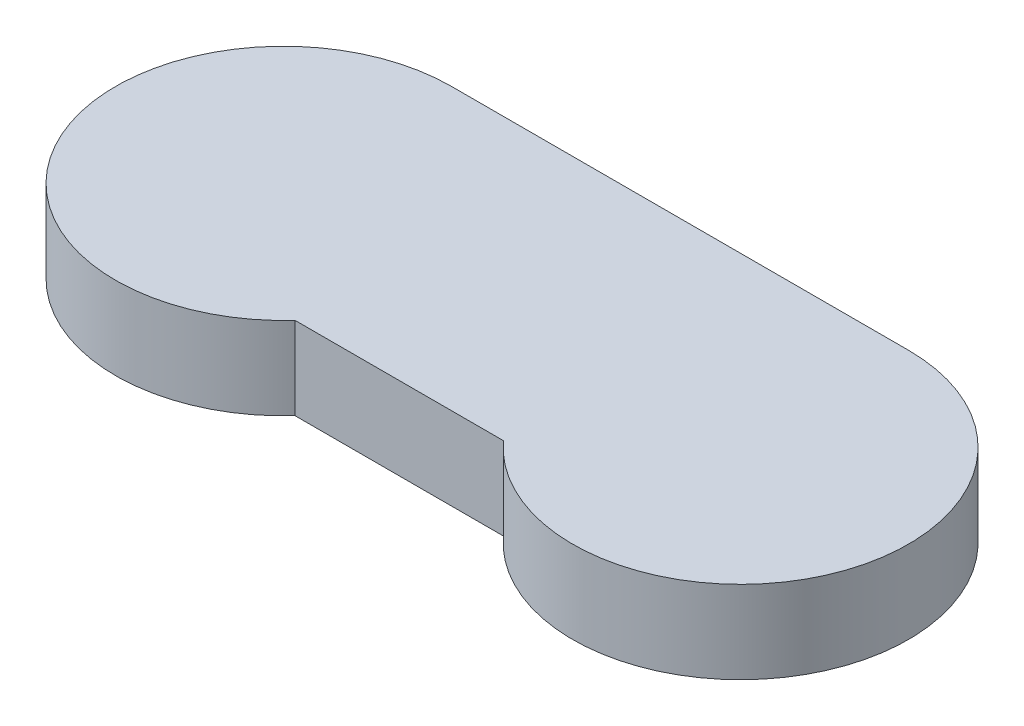
SolidWorks part; units mm, degrees
ref_plane "Front Plane" through (0, 0, 0) normal (0, 0, 1) x (1, 0, 0)
ref_plane "Top Plane" through (0, 0, 0) normal (0, 1, 0) x (1, 0, 0)
ref_plane "Right Plane" through (0, 0, 0) normal (1, 0, 0) x (0, 0, -1)
sketch "Sketch1" plane through (0, 0, 0) normal (0, 1, 0) x (1, 0, 0)
  line L1 (72, -30.5) -> (-72, -30.5) construction
  line L3 (41.5, 30.5) -> (-41.5, 30.5)
  line L5 (72, -30.5) -> (-72, 30.5) construction
  line L6 (72, 30.5) -> (-11.3836, -4.8222) construction
  line L7 (-18.9168, -20.5) -> (18.9168, -20.5)
  line L8 (-58.9884, -24.9881) -> (-72, -30.5) construction
  arc A0 (-41.5, 30.5) -> (-18.9168, -20.5) centre (-41.5, 0) ccw
  arc A1 (18.9168, -20.5) -> (41.5, 30.5) centre (41.5, 0) ccw
  point P0 (0, 0)
  dimension "D4" = 61
  dimension "D2" = 83
  dimension "D1" = 144
  dimension "D3" = 61
  dimension "D6" = 10
extrude "Boss-Extrude1" add sketch "Sketch1" along normal blind 15
sketch "Sketch2" plane through (0, 0, 0) normal (0, 1, 0) x (1, 0, 0)
  line L6 (41.5, 25.5) -> (-41.5, 25.5)
  line L7 (-21.2515, -15.5) -> (21.2515, -15.5)
  line L8 (41.5, 25.5) -> (-41.5, 25.5)
  line L9 (-21.2515, -15.5) -> (21.2515, -15.5)
  arc A8 (21.2515, -15.5) -> (41.5, 25.5) centre (41.5, 0) ccw
  arc A9 (-41.5, 25.5) -> (-21.2515, -15.5) centre (-41.5, 0) ccw
  arc A10 (21.2515, -15.5) -> (41.5, 25.5) centre (41.5, 0) ccw
  arc A11 (-41.5, 25.5) -> (-21.2515, -15.5) centre (-41.5, 0) ccw
  dimension "D1" = 5
extrude "Cut-Extrude1" cut sketch "Sketch2" along normal blind 10
